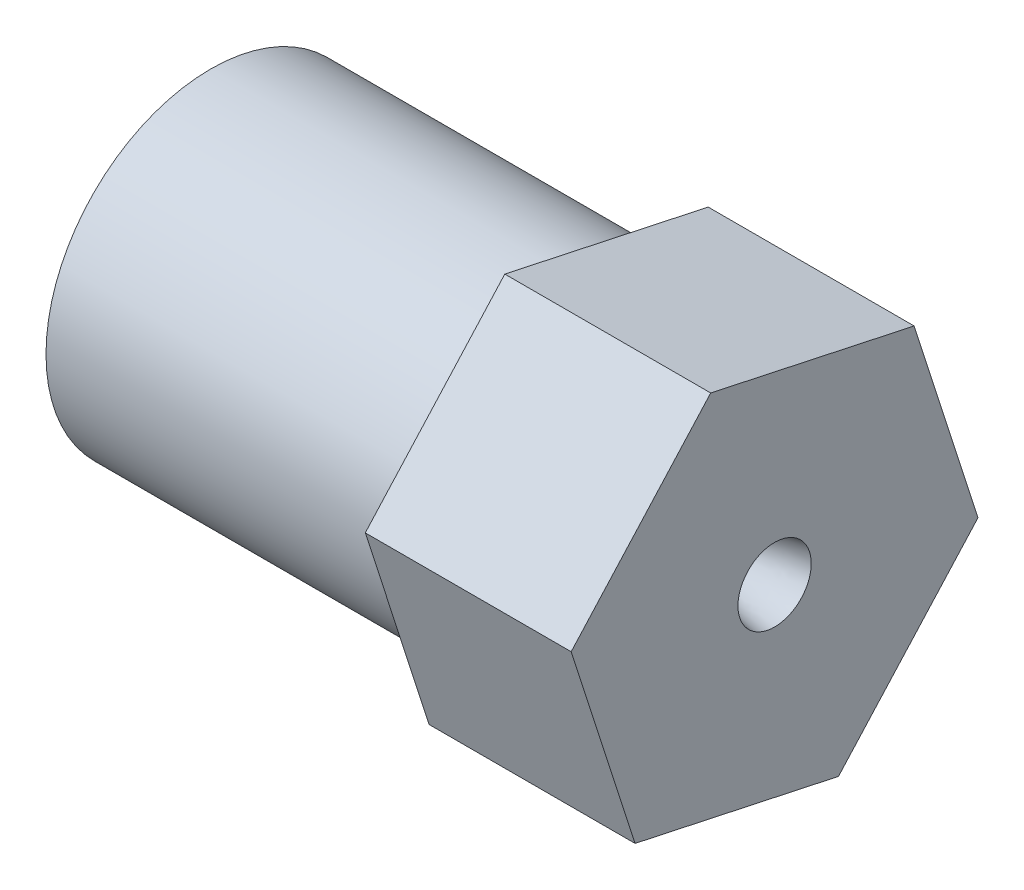
SolidWorks part; units mm, degrees
ref_plane "Front Plane" through (0, 0, 0) normal (0, 0, 1) x (1, 0, 0)
ref_plane "Top Plane" through (0, 0, 0) normal (0, 1, 0) x (1, 0, 0)
ref_plane "Right Plane" through (0, 0, 0) normal (1, 0, 0) x (0, 0, -1)
sketch "Sketch1" plane through (0, 0, 0) normal (0, 0, 1) x (1, 0, 0)
  line L0 (0, 0) -> (3.0288, 0) construction
  line L1 (0.2085, 1.5608) -> (3.0288, 2.5873) construction
  line L2 (-1.6164, 2.1936) -> (-2.938, 3.5151)
  line L3 (-31.75, 4.445) -> (-31.75, 10.16) construction
  line L4 (-5.183, 4.445) -> (-31.75, 4.445) construction
  line L5 (-31.75, 10.16) -> (-9.6712, 10.16)
  line L6 (3.0288, 10.16) -> (3.0288, 2.2605)
  line L7 (3.0288, 2.2605) -> (13.0643, 3.6709) construction
  line L8 (-9.6712, 10.16) -> (3.0288, 10.16)
  line L9 (-5.183, 4.445) -> (-13.462, 4.445)
  line L10 (-19.939, 5.461) -> (-19.939, 6.8199)
  line L11 (-20.066, 6.9469) -> (-24.892, 6.9469)
  line L12 (-24.892, 6.9469) -> (-24.892, 7.8994)
  line L13 (-25.019, 8.0264) -> (-31.115, 8.0264)
  line L14 (-31.75, 10.16) -> (-31.75, 8.6614)
  line L15 (0, 0) -> (-31.75, 0) construction
  line L16 (-13.462, 4.445) -> (-13.462, 4.699)
  line L17 (-13.589, 4.826) -> (-19.304, 4.826)
  arc A0 (-1.6164, 2.1936) -> (0, 1.524) centre (0, 3.81) ccw
  arc A1 (0, 1.524) -> (0.2085, 1.5608) centre (0, 2.1336) ccw
  arc A2 (-2.938, 3.5151) -> (-5.183, 4.445) centre (-5.183, 1.27) ccw
  arc A3 (-31.115, 8.0264) -> (-31.75, 8.6614) centre (-31.115, 8.6614) cw
  arc A4 (-19.304, 4.826) -> (-19.939, 5.461) centre (-19.304, 5.461) cw
  arc A5 (-13.462, 4.699) -> (-13.589, 4.826) centre (-13.589, 4.699) ccw
  arc A6 (-19.939, 6.8199) -> (-20.066, 6.9469) centre (-20.066, 6.8199) ccw
  arc A7 (-24.892, 7.8994) -> (-25.019, 8.0264) centre (-25.019, 7.8994) ccw
  parabola Q0 (3.0288, 2.2605) -> (0.2085, 1.5608) focus (2.5332, -4.8263) apex (0.2085, 1.5608)
  point P30 (-31.75, 8.0264)
  point P39 (-24.892, 8.0264)
  dimension "D3" = 2.286
  dimension "D4" = 0.6096
  dimension "D11" = 3.175
  dimension "D12" = 8
  dimension "D14" = 6.9469
  dimension "D20" = 0.635
  dimension "D21" = 0.127
  dimension "D2" = 3.0288
  dimension "D5" = 2.2605
  dimension "D6" = 20
  dimension "D7" = 45
  dimension "D8" = 8.0264
  dimension "D9" = 31.75
  dimension "D10" = 10.16
  dimension "D13" = 12.7
  dimension "D15" = 4.445
  dimension "D16" = 6.858
  dimension "D17" = 11.811
  dimension "D18" = 18.288
  dimension "D19" = 4.826
  dimension "D22" = 1.524
revolve "Revolve1" add sketch "Sketch1" angle 360 about L0
sketch "Sketch4" plane through (3.0288, 0, 0) normal (1, 0, 0) x (0, 0, -1)
  line L1 (3.9404, -12.2116) -> (12.5458, -2.6933)
  line L2 (12.5458, -2.6933) -> (8.6054, 9.5183)
  line L3 (8.6054, 9.5183) -> (-3.9404, 12.2116)
  line L4 (-3.9404, 12.2116) -> (-12.5458, 2.6933)
  line L5 (-12.5458, 2.6933) -> (-8.6054, -9.5183)
  line L6 (-8.6054, -9.5183) -> (3.9404, -12.2116)
  circle A0 centre (0, 0) radius 10.16
  circle A1 centre (0, 0) radius 10.16 construction
  circle A2 centre (0, 0) radius 11.1125 construction
  circle M1 centre (0, 0) radius 10.16
  dimension "D1" = 22.225
extrude "Boss-Extrude1" add sketch "Sketch4" against normal blind 12.7 contours L4 L5 M1 | L3 L4 M1 | L2 L3 M1 | L1 L2 M1 | L6 L1 M1 | L5 L6 M1
fillet "Fillet1" radius 0.635 1 edges at (-9.6712, 0, -10.16)
equation "\"D3@Sketch1\" = 1.5 * \"D22@Sketch1\""
equation "\"D4@Sketch1\"  = .4 * \"D22@Sketch1\""
equation "\"D5@Sketch1\"=\"D22@Sketch1\" * ( \"er\") ^ .5"
equation "\"er\"= 2.2"
